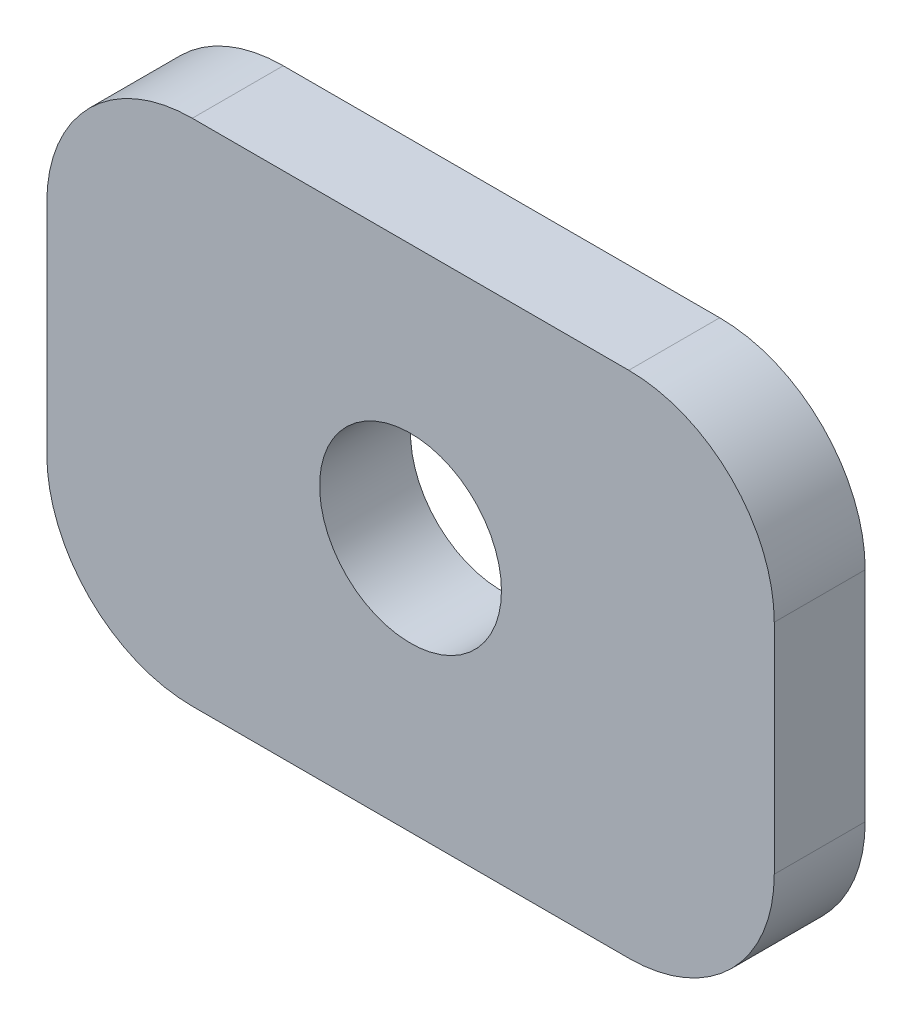
SolidWorks part; units mm, degrees
ref_plane "Front Plane" through (0, 0, 0) normal (0, 0, 1) x (1, 0, 0)
ref_plane "Top Plane" through (0, 0, 0) normal (0, 1, 0) x (1, 0, 0)
ref_plane "Right Plane" through (0, 0, 0) normal (1, 0, 0) x (0, 0, -1)
sketch "Sketch1" plane through (0, 0, 0) normal (0, 0, 1) x (1, 0, 0)
  line L1 (0, 0) -> (25.4, 0)
  line L2 (0, 0) -> (0, -17.78)
  line L3 (0, -17.78) -> (25.4, -17.78)
  line L4 (25.4, 0) -> (25.4, -17.78)
extrude "Boss-Extrude1" add sketch "Sketch1" along normal blind 3.175
hole_wizard "Hole1" positions "Sketch3" profile "Sketch2" legacy end condition through all
sketch "Sketch3" plane through (0, 0, 3.175) normal (0, 0, 1) x (1, 0, 0)
  point P0 (12.7, -8.89)
sketch "Sketch2" plane through (12.7, -8.89, 3.175) normal (1, 0, 0) x (0, -1, 0)
  line L0 (0, 0) -> (0, 3.175)
  line L1 (0, 3.175) -> (3.175, 3.175)
  line L2 (3.175, 3.175) -> (3.175, 0)
  line L3 (3.175, 0) -> (0, 0)
  line L4 (0, 110) -> (0, -10) construction
  dimension "Diameter" = 6.35
  dimension "Depth" = 3.175
fillet "Fillet1" radius 5.08 4 edges at (0, -17.78, 1.5875) (25.4, -17.78, 1.5875) (0, 0, 1.5875) (25.4, 0, 1.5875)
